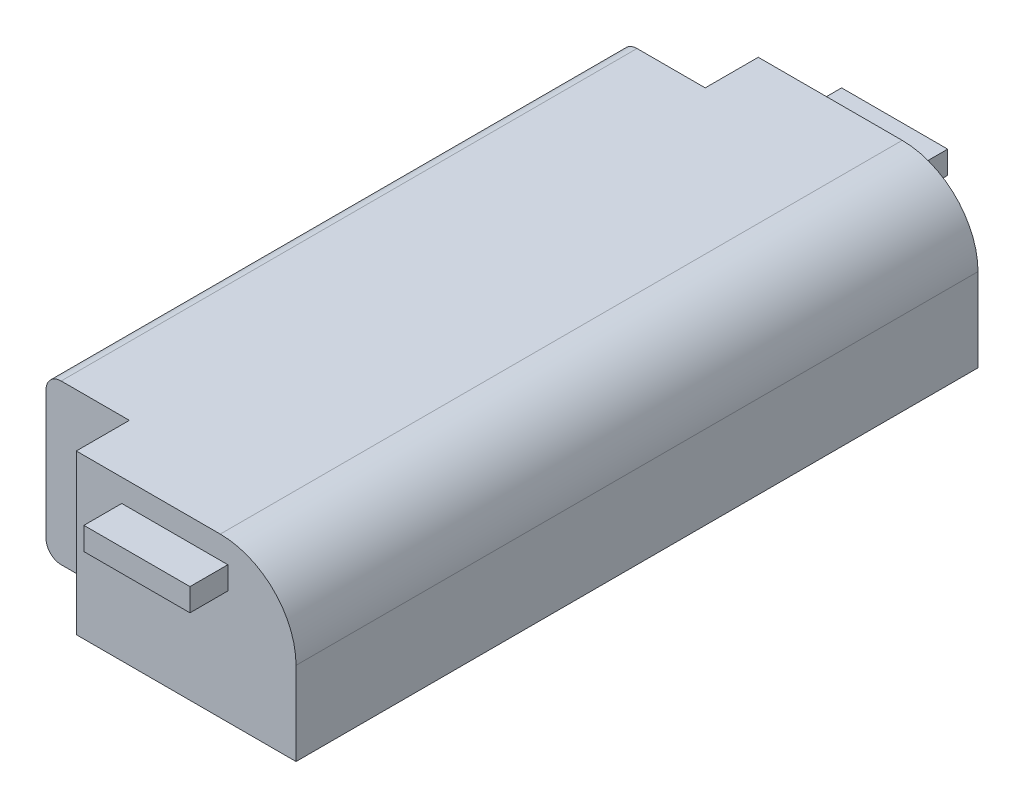
SolidWorks part; units mm, degrees
ref_plane "Front Plane" through (0, 0, 0) normal (0, 0, 1) x (1, 0, 0)
ref_plane "Top Plane" through (0, 0, 0) normal (0, 1, 0) x (1, 0, 0)
ref_plane "Right Plane" through (0, 0, 0) normal (1, 0, 0) x (0, 0, -1)
sketch "Sketch1" plane through (0, 0, 0) normal (0, 0, 1) x (1, 0, 0)
  line L0 (0, 0) -> (0, -20.32)
  line L1 (0, -20.32) -> (-7.62, -20.32)
  line L2 (-7.62, -20.32) -> (-7.62, 6.35)
  line L3 (-7.62, 6.35) -> (43.18, 6.35)
  line L4 (43.18, 6.35) -> (43.18, -20.32)
  line L7 (43.18, -20.32) -> (6.35, -20.32)
  line L8 (6.35, -20.32) -> (6.35, 0)
  line L9 (6.35, 0) -> (0, 0)
  dimension "D1" = 6.35
  dimension "D2" = 7.62
  dimension "D3" = 20.32
  dimension "D4" = 6.35
  dimension "D5" = 50.8
extrude "Boss-Extrude1" add sketch "Sketch1" along normal blind 96.52
ref_plane "Plane2" through (0, 0, 48.26) normal (0, 0, -1) x (-1, 0, 0)
sketch "Sketch3" plane through (0, 0, 96.52) normal (0, 0, 1) x (1, 0, 0)
  line L1 (6.35, -20.32) -> (43.18, -20.32)
  line L2 (6.35, -20.32) -> (6.35, 6.35)
  line L3 (6.35, 6.35) -> (43.18, 6.35)
  line L4 (43.18, -20.32) -> (43.18, 6.35)
extrude "Boss-Extrude3" add sketch "Sketch3" along normal blind 8.89
sketch "Sketch2" plane through (0, 0, 105.41) normal (0, 0, -1) x (-1, 0, 0)
  line L0 (-43.18, 6.35) -> (7.62, 6.35) construction
  line L1 (-31.75, -1.27) -> (-13.97, -1.27)
  line L2 (-31.75, -1.27) -> (-31.75, 2.54)
  line L3 (-31.75, 2.54) -> (-13.97, 2.54)
  line L4 (-13.97, -1.27) -> (-13.97, 2.54)
  line L6 (-6.35, 0) -> (-6.35, -20.32) construction
  dimension "D1" = 3.81
  dimension "D2" = 17.78
  dimension "D3" = 3.81
  dimension "D4" = 7.62
extrude "Boss-Extrude4" add sketch "Sketch2" against normal blind 6.35
mirror "Mirror2" about plane through (0, 0, 48.26) normal (0, 0, -1) of "Boss-Extrude3", "Boss-Extrude4"
fillet "Fillet1" radius 12.7 1 edges at (43.18, 6.35, 48.26)
fillet "Fillet2" radius 2.54 2 edges at (-7.62, -20.32, 48.26) (-7.62, 6.35, 48.26)
